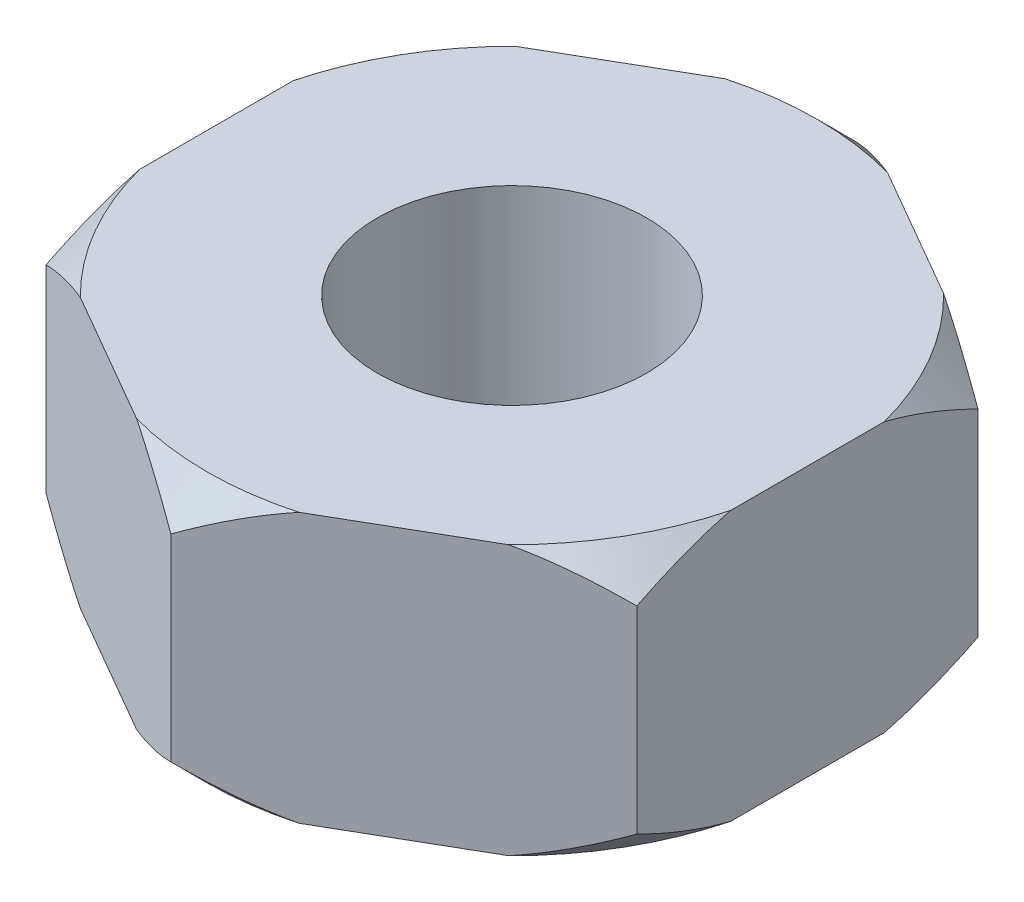
SolidWorks part; units mm, degrees
ref_plane "Front Plane" through (0, 0, 0) normal (0, 0, 1) x (1, 0, 0)
ref_plane "Top Plane" through (0, 0, 0) normal (0, 1, 0) x (1, 0, 0)
ref_plane "Right Plane" through (0, 0, 0) normal (1, 0, 0) x (0, 0, -1)
sketch "Sketch3" plane through (0, 0, 0) normal (0, 1, 0) x (1, 0, 0)
  line L1 (0, -19) -> (16.4545, -9.5)
  line L2 (16.4545, -9.5) -> (16.4545, 9.5)
  line L3 (16.4545, 9.5) -> (0, 19)
  line L4 (0, 19) -> (-16.4545, 9.5)
  line L5 (-16.4545, 9.5) -> (-16.4545, -9.5)
  line L6 (-16.4545, -9.5) -> (0, -19)
  circle A0 centre (0, 0) radius 16.4545 construction
  dimension "D1" = 19
extrude "Boss-Extrude1" add sketch "Sketch3" along normal blind 15
sketch "Sketch4" plane through (0, 15, 0) normal (0, 1, 0) x (1, 0, 0)
  circle A0 centre (0, 0) radius 7.5
  dimension "D1" = 15
extrude "Cut-Extrude1" cut sketch "Sketch4" against normal through all
sketch "Sketch6" plane through (0, 0, 0) normal (1, 0, 0) x (0, 0, -1)
  line L0 (16.2224, 15.7776) -> (21.2224, 10.7776)
  line L1 (21.2224, 10.7776) -> (21.2224, 15.7776)
  line L2 (21.2224, 15.7776) -> (16.2224, 15.7776)
  line L3 (19, 15) -> (17, 15) construction
  line L4 (9.5, 15) -> (19, 15) construction
  line L5 (0, 0) -> (0, 15) construction
  line L6 (-9.5, 15) -> (9.5, 15) construction
  dimension "D1" = 5
  dimension "D2" = 5
  dimension "D3" = 2
revolve "Cut-Revolve1" cut sketch "Sketch6" angle 360 about L5
sketch "Sketch8" plane through (0, 0, 0) normal (1, 0, 0) x (0, 0, -1)
  line L0 (16.3034, -0.6966) -> (21.3034, 4.3034)
  line L1 (21.3034, 4.3034) -> (21.3034, -0.6966)
  line L2 (21.3034, -0.6966) -> (16.3034, -0.6966)
  line L3 (19, 0) -> (17, 0) construction
  line L4 (9.5, 0) -> (19, 0) construction
  line L5 (0, 0) -> (0, 15) construction
  line L6 (-4.272, 15) -> (4.272, 15) construction
  dimension "D1" = 5
  dimension "D2" = 5
  dimension "D3" = 2
revolve "Cut-Revolve2" cut sketch "Sketch8" angle 360 about L5
